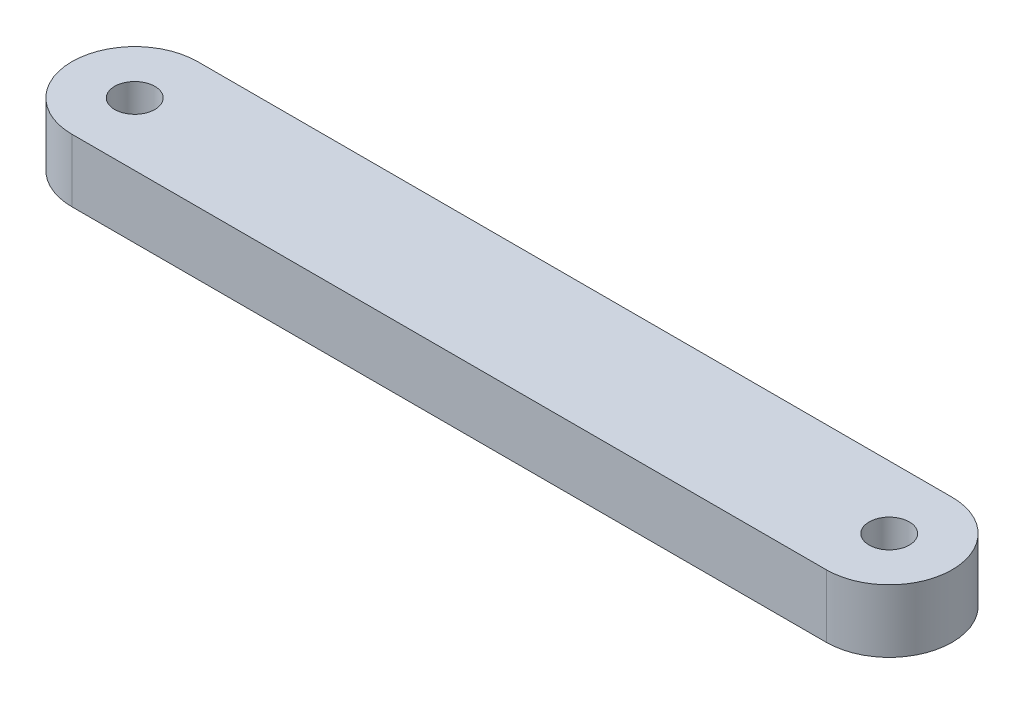
SolidWorks part; units mm, degrees
ref_plane "正面" through (0, 0, 0) normal (0, 0, 1) x (1, 0, 0)
ref_plane "平面" through (0, 0, 0) normal (0, 1, 0) x (1, 0, 0)
ref_plane "右側面" through (0, 0, 0) normal (1, 0, 0) x (0, 0, -1)
sketch "ｽｹｯﾁ1" plane through (0, 0, 0) normal (0, 1, 0) x (1, 0, 0)
  line L0 (0, 0) -> (110, 0) construction
  line L1 (0, -5) -> (60, -5)
  line L3 (0, 5) -> (60, 5)
  circle A0 centre (0, 0) radius 1.6
  circle A1 centre (60, 0) radius 1.6
  arc A2 (0, 5) -> (0, -5) centre (0, 0) ccw
  arc A3 (60, -5) -> (60, 5) centre (60, 0) ccw
  dimension "D5" = 3.2
  dimension "D1" = 5
  dimension "D2" = 10
  dimension "D4" = 60
extrude "ﾎﾞｽ - 押し出し1" add sketch "ｽｹｯﾁ1" along normal blind 5
